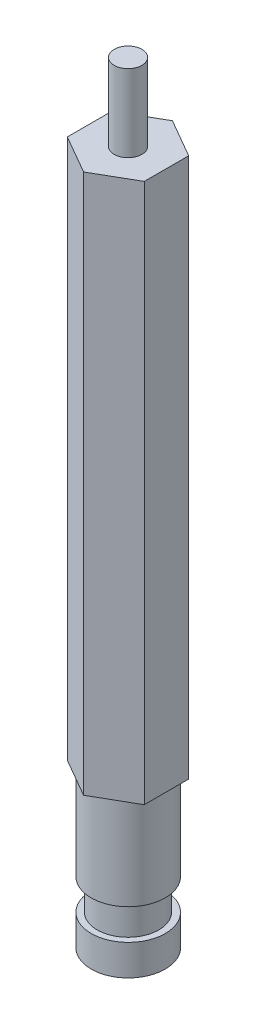
SolidWorks part; units mm, degrees
ref_plane "Front Plane" through (0, 0, 0) normal (0, 0, 1) x (1, 0, 0)
ref_plane "Top Plane" through (0, 0, 0) normal (0, 1, 0) x (1, 0, 0)
ref_plane "Right Plane" through (0, 0, 0) normal (1, 0, 0) x (0, 0, -1)
sketch "Sketch1" plane through (0, 0, 0) normal (0, 1, 0) x (1, 0, 0)
  line L2 (3.3102, -4.4201) -> (3.3102, -0.7625)
  line L3 (3.3102, -0.7625) -> (0.1408, 1.0631)
  line L4 (0.1408, 1.0631) -> (-3.0287, -0.7625)
  line L5 (-3.0287, -0.7625) -> (-3.0287, -4.4201)
  line L6 (-3.0287, -4.4201) -> (0.1408, -6.2457)
  line L7 (0.1408, -6.2457) -> (3.3102, -4.4201)
  point P8 (3.3102, -2.5913)
extrude "Boss-Extrude1" add sketch "Sketch1" along normal blind 63.5
sketch "Sketch2" plane through (0, 63.5, 0) normal (0, 1, 0) x (1, 0, 0)
  circle A0 centre (0.1463, -2.5913) radius 1.143
extrude "Cut-Extrude1" cut sketch "Sketch2" against normal blind 6.35 flip side to cut
sketch "Sketch3" plane through (0, 0, 0) normal (0, -1, 0) x (1, 0, 0)
  circle A0 centre (0.1526, 2.5845) radius 3.048
extrude "Cut-Extrude2" cut sketch "Sketch3" against normal blind 12.7 flip side to cut
ref_plane "Plane1" through (0, 2.54, 0) normal (0, -1, 0) x (-1, 0, 0)
sketch "Sketch4" plane through (0, 2.54, 0) normal (0, -1, 0) x (-1, 0, 0)
  circle A0 centre (-0.1408, -2.5913) radius 2.54
extrude "Cut-Extrude3" cut sketch "Sketch4" against normal blind 2.54 flip side to cut
